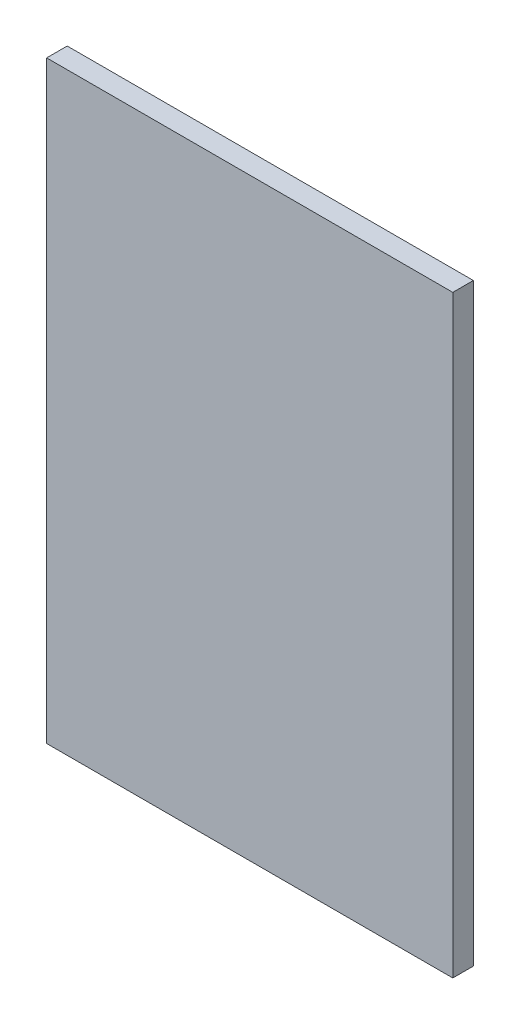
SolidWorks part; units mm, degrees
ref_plane "Front Plane" through (0, 0, 0) normal (0, 0, 1) x (1, 0, 0)
ref_plane "Top Plane" through (0, 0, 0) normal (0, 1, 0) x (1, 0, 0)
ref_plane "Right Plane" through (0, 0, 0) normal (1, 0, 0) x (0, 0, -1)
sketch "Sketch1" plane through (0, 0, 0) normal (0, 0, 1) x (1, 0, 0)
  line L1 (-125.4125, -183.3626) -> (125.4125, -183.3626)
  line L2 (-125.4125, -183.3626) -> (-125.4125, 183.3626)
  line L3 (-125.4125, 183.3626) -> (125.4125, 183.3626)
  line L4 (125.4125, -183.3626) -> (125.4125, 183.3626)
  line L5 (-125.4125, -183.3626) -> (125.4125, 183.3626) construction
  line L6 (-125.4125, 183.3626) -> (125.4125, -183.3626) construction
  point P0 (0, 0)
  dimension "D1" = 366.7252
  dimension "D2" = 250.825
extrude "Boss-Extrude1" add sketch "Sketch1" along normal mid plane 12.7
